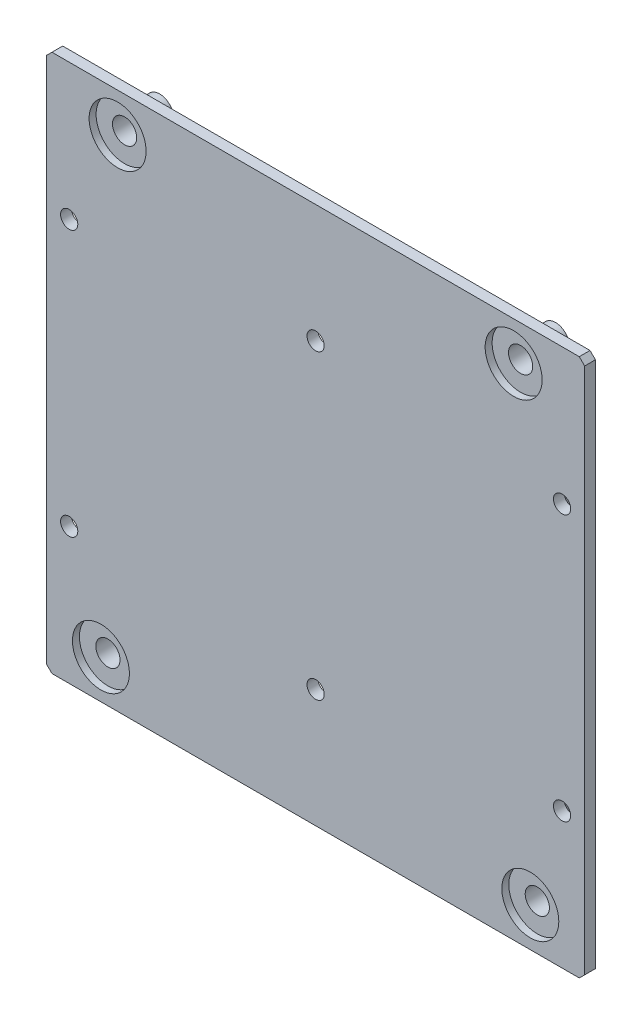
SolidWorks part; units mm, degrees
material "PET"
ref_plane "Front Plane" through (0, 0, 0) normal (1, 0, 0) x (0, 1, 0)
ref_plane "Top Plane" through (0, 0, 0) normal (0, 0, 1) x (0, 1, 0)
ref_plane "Right Plane" through (0, 0, 0) normal (0, 1, 0) x (-1, 0, 0)
sketch "Sketch1" plane through (0, 0, 0) normal (0, 0, 1) x (0, 1, 0)
  line L1 (0, 0) -> (100, 0)
  line L2 (0, 0) -> (0, 100)
  line L3 (0, 100) -> (100, 100)
  line L4 (100, 0) -> (100, 100)
  dimension "D1" = 100
extrude "Boss-Extrude1" add sketch "Sketch1" along normal blind 2
chamfer "Chamfer1" distance 1 angle 45 4 edges at (-100, 0, 1) (0, 100, 1) (-100, 100, 1) (0, 0, 1)
sketch "Sketch2" plane through (0, 0, 0) normal (0, 0, -1) x (1, 0, 0)
  line L0 (0, -1) -> (0, -99) construction
  line L1 (-7.2, -7.2) -> (-92.8, -7.2)
  line L2 (-7.2, -7.2) -> (-7.2, -92.8)
  line L3 (-7.2, -92.8) -> (-92.8, -92.8)
  line L4 (-92.8, -7.2) -> (-92.8, -92.8)
  line L5 (-99, 0) -> (-1, 0) construction
  dimension "D1" = 7.2
  dimension "D2" = 7.2
  dimension "D3" = 85.6
extrude "Extrude-Thin1" add sketch "Sketch2" along normal blind 3 thin thin type one direction reverse wall 2
sketch "Sketch3" plane through (0, 0, 0) normal (0, 0, -1) x (1, 0, 0)
  line L0 (-7.2, -89.4) -> (-7.2, -92.8)
  line L1 (-7.2, -92.8) -> (-7.2, -7.2) construction
  line L3 (-7.2, -92.8) -> (-10.617, -92.8)
  line L4 (-92.8, -92.8) -> (-7.2, -92.8) construction
  line L5 (-16.6, -92.8) -> (-16.6, -92.4)
  line L6 (-13.6, -89.4) -> (-7.2, -89.4)
  line L7 (-15.8131, -92.8) -> (-16.6, -92.8)
  line L17 (-14, -7.2) -> (-12.9, -7.2)
  line L18 (-7.2, -7.2) -> (-92.8, -7.2) construction
  line L21 (-7.2, -9.8) -> (-7.2, -10.6)
  line L23 (-7.2, -10.6) -> (-11, -10.6)
  line L24 (-14, -7.6) -> (-14, -7.2)
  arc A0 (-15.8131, -92.8) -> (-10.617, -92.8) centre (-13.215, -92.9) ccw
  arc A2 (-13.6, -89.4) -> (-16.6, -92.4) centre (-13.6, -92.4) ccw
  arc A5 (-6.7805, -7.8) -> (-7.2, -9.8) centre (-12.2794, -7.6906) cw
  arc A6 (-14, -7.6) -> (-11, -10.6) centre (-11, -7.6) ccw
  arc A7 (-12.9, -7.2) -> (-6.7805, -7.8) centre (-9.8524, -7.6241) cw
  point P14 (-16.6, -89.4)
  point P31 (-14, -10.6)
  dimension "D3" = 5.2
  dimension "D4" = 3
  dimension "D6" = 3.4
  dimension "D7" = 3.0769
  dimension "D8" = 2
  dimension "D9" = 5.5
  dimension "D12" = 3
  dimension "D1" = 9.4
  dimension "D2" = 3.4
  dimension "D5" = 6.8
  dimension "D10" = 1.1
  dimension "D11" = 0.8
  dimension "D13" = 0.4241
extrude "Boss-Extrude2" add sketch "Sketch3" along normal blind 5.8
sketch "Sketch4" plane through (0, 0, 2) normal (0, 0, 1) x (1, 0, 0)
  line L2 (-7.2, 92.8) -> (-7.2, 9.8) construction
  line L5 (-10.617, 92.8) -> (-7.2, 92.8) construction
  line L6 (-12.9, 7.2) -> (-92.8, 7.2) construction
  line L7 (0, 1) -> (0, 99) construction
  point P0 (-13.2, 92.8)
  point P18 (-10.1, 7.2)
  dimension "D1" = 6
  dimension "D2" = 10.1
hole_wizard "Hole1" positions "Sketch4" profile "Sketch5" legacy end condition through all
sketch "Sketch5" plane through (-13.2, 92.8, 2) normal (1, 0, 0) x (0, -1, 0)
  line L0 (0, 0) -> (0, 7.8)
  line L1 (0, 7.8) -> (2.25, 7.8)
  line L3 (2.25, 7.8) -> (2.25, 1.3)
  line L4 (2.25, 1.3) -> (5.295, 1.3)
  line L5 (5.295, 1.3) -> (5.295, 0)
  line L7 (5.295, 0) -> (0, 0)
  line L11 (0, -6.35) -> (0, 107.95) construction
  dimension "Thru Hole Dia." = 4.5
  dimension "Thru Hole Depth" = 7.8
  dimension "C'Bore Dia." = 10.59
  dimension "C'Bore Depth" = 1.3
ref_plane "Plane1" through (-50, 0, 0) normal (1, 0, 0) x (0, 0, -1)
mirror "Mirror1" about plane through (-50, 0, 0) normal (1, 0, 0) of "Boss-Extrude2", "Hole1"
sketch "Sketch6" plane through (0, 0, 0) normal (0, 0, -1) x (1, 0, 0)
  line L0 (-83.8623, -90.8) -> (-16.1377, -90.8) construction
  line L1 (-90.8, -10.6) -> (-90.8, -89.4) construction
  line L3 (-13.5377, -9.2) -> (-86.4623, -9.2) construction
  line L4 (-9.2, -89.4) -> (-9.2, -10.6) construction
  circle A0 centre (-71.1, -88.57) radius 3.5
  circle A1 centre (-71.1, -57.67) radius 3.5
  circle A2 centre (-30.4, -57.67) radius 3.5
  circle A3 centre (-30.4, -88.57) radius 3.5
  circle A4 centre (-22.4, -48.3) radius 3.5
  circle A5 centre (-60.4, -48.3) radius 3.5
  circle A6 centre (-60.4, -11.3) radius 3.5
  circle A7 centre (-22.4, -11.3) radius 3.5
  dimension "D1" = 7
  dimension "D2" = 30.9
  dimension "D3" = 40.7
  dimension "D4" = 38
  dimension "D5" = 37
  dimension "D6" = 2.23
  dimension "D7" = 19.7
  dimension "D8" = 2.1
  dimension "D9" = 13.2
extrude "Boss-Extrude3" add sketch "Sketch6" along normal blind 5
extrude "Cut-Extrude2" cut sketch "Sketch10" against normal through all
sketch "Sketch10" plane through (0, 0, 2) normal (0, 0, 1) x (1, 0, 0)
  line L0 (-1, 100) -> (-99, 100) construction
  line L1 (0, 1) -> (0, 99) construction
  line L2 (-100, 50) -> (0, 50) construction
  line L3 (-100, 99) -> (-100, 1) construction
  circle A0 centre (-50, 78.05) radius 1.6
  circle A1 centre (-4.2, 74.7) radius 1.6
  circle A2 centre (-95.8, 74.7) radius 1.6
  circle A3 centre (-95.8, 25.3) radius 1.6
  circle A4 centre (-4.2, 25.3) radius 1.6
  circle A5 centre (-50, 21.95) radius 1.6
  dimension "D1" = 3.2
  dimension "D2" = 91.6
  dimension "D3" = 21.95
  dimension "D4" = 45.8
  dimension "D5" = 50
  dimension "D6" = 25.3
sketch "Sketch7" plane through (0, 0, 0) normal (0, 0, -1) x (1, 0, 0)
  line L0 (-9.2, -48.3) -> (-90.8, -48.3)
  line L1 (-30.4, -92.07) -> (-30.4, -9.2)
  line L2 (-25.2, -9.2) -> (-57.6, -9.2) construction
  line L3 (-22.4, -7.8) -> (-22.4, -90.8)
  line L4 (-9.2, -89.4) -> (-9.2, -10.6) construction
  line L5 (-27.7024, -90.8) -> (-16.1377, -90.8) construction
  line L6 (-90.8, -10.6) -> (-90.8, -89.4) construction
  line L7 (-9.2, -57.67) -> (-90.8, -57.67)
  line L8 (-71.1, -92.07) -> (-71.1, -9.2)
  line L9 (-63.2, -9.2) -> (-86.4623, -9.2) construction
  line L10 (-60.4, -7.8) -> (-60.4, -90.8)
  line L11 (-68.4024, -90.8) -> (-33.0976, -90.8) construction
  line L12 (-90.8, -70.67) -> (-9.2, -70.67)
  line L13 (-90.8, -30.3) -> (-9.2, -30.3)
  circle A0 centre (-71.1, -57.67) radius 3.5 construction
  circle A1 centre (-71.1, -88.57) radius 3.5 construction
  circle A2 centre (-30.4, -88.57) radius 3.5 construction
  circle A3 centre (-30.4, -57.67) radius 3.5 construction
  circle A4 centre (-22.4, -11.3) radius 3.5 construction
  circle A5 centre (-60.4, -11.3) radius 3.5 construction
  circle A6 centre (-60.4, -48.3) radius 3.5 construction
  circle A7 centre (-22.4, -48.3) radius 3.5 construction
  circle A8 centre (-71.1, -57.67) radius 3.5 construction
  circle A9 centre (-71.1, -88.57) radius 3.5 construction
  circle A10 centre (-30.4, -88.57) radius 3.5 construction
  circle A11 centre (-30.4, -57.67) radius 3.5 construction
  circle A12 centre (-22.4, -11.3) radius 3.5 construction
  circle A13 centre (-60.4, -11.3) radius 3.5 construction
  circle A14 centre (-60.4, -48.3) radius 3.5 construction
  circle A15 centre (-22.4, -48.3) radius 3.5 construction
  dimension "D1" = 18
  dimension "D2" = 13
extrude "Extrude-Thin2" add sketch "Sketch7" along normal blind 3 thin thin type mid plane wall 1.5
sketch "Sketch9" plane through (0, 0, -5) normal (0, 0, -1) x (1, 0, 0)
  circle A0 centre (-60.4, -11.3) radius 2
  circle A1 centre (-22.4, -11.3) radius 2
  circle A2 centre (-22.4, -48.3) radius 2
  circle A3 centre (-30.4, -57.67) radius 2
  circle A4 centre (-60.4, -48.3) radius 2
  circle A5 centre (-71.1, -88.57) radius 2
  circle A6 centre (-30.4, -88.57) radius 2
  circle A7 centre (-71.1, -57.67) radius 2
  dimension "D1" = 4
extrude "Cut-Extrude1" cut sketch "Sketch9" against normal blind 5
